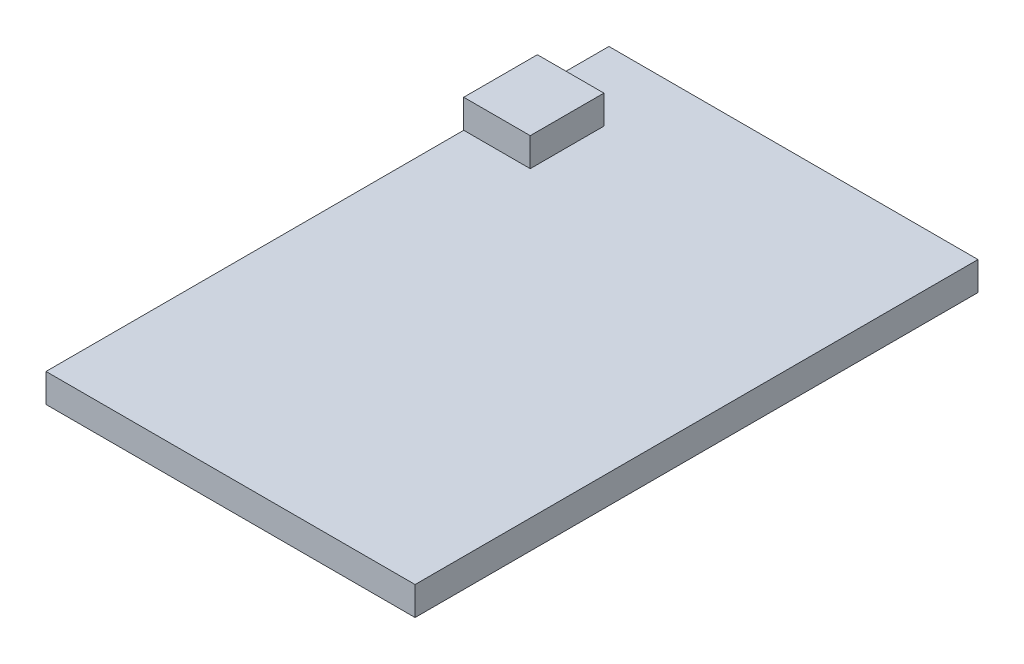
SolidWorks part; units mm, degrees
ref_plane "前视基准面" through (0, 0, 0) normal (0, 0, 1) x (1, 0, 0)
ref_plane "上视基准面" through (0, 0, 0) normal (0, 1, 0) x (1, 0, 0)
ref_plane "右视基准面" through (0, 0, 0) normal (1, 0, 0) x (0, 0, -1)
other "Configuration Table"
sketch "草图1" plane through (0, 0, 0) normal (0, 1, 0) x (1, 0, 0)
  line L1 (-25.8, 39.35) -> (25.8, 39.35)
  line L2 (-25.8, 39.35) -> (-25.8, -39.35)
  line L3 (-25.8, -39.35) -> (25.8, -39.35)
  line L4 (25.8, 39.35) -> (25.8, -39.35)
  line L5 (-25.8, 39.35) -> (25.8, -39.35) construction
  line L6 (-25.8, -39.35) -> (25.8, 39.35) construction
  point P0 (0, 0)
  dimension "D1" = 78.7
  dimension "D2" = 51.6
extrude "凸台-拉伸1" add sketch "草图1" along normal blind 4
sketch "草图2" plane through (0, 4, 0) normal (0, 1, 0) x (1, 0, 0)
  line L0 (25.8, 39.35) -> (-25.8, 39.35) construction
  line L1 (-25.8, 29.35) -> (-16.5, 29.35)
  line L2 (-25.8, 29.35) -> (-25.8, 19.05)
  line L3 (-25.8, 19.05) -> (-16.5, 19.05)
  line L4 (-16.5, 29.35) -> (-16.5, 19.05)
  line L5 (-25.8, 29.35) -> (-16.5, 19.05) construction
  line L6 (-25.8, 19.05) -> (-16.5, 29.35) construction
  line L7 (-25.8, 39.35) -> (-25.8, -39.35) construction
  point P0 (-21.15, 24.2)
  dimension "D1" = 10
  dimension "D2" = 10.3
  dimension "D3" = 9.3
extrude "凸台-拉伸2" add sketch "草图2" along normal blind 4
